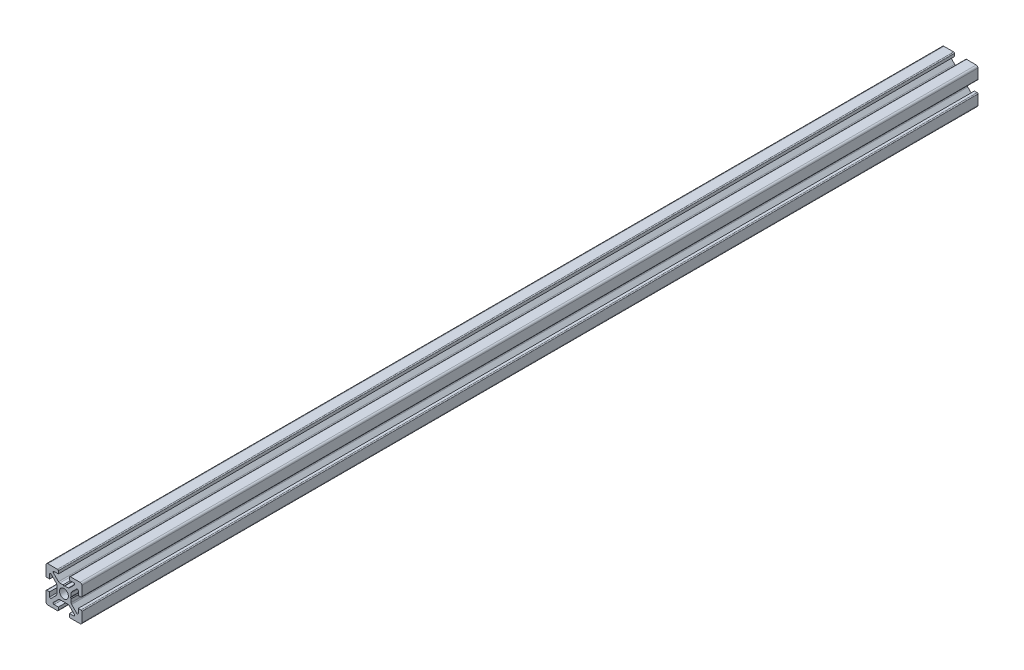
SolidWorks part; units mm, degrees
ref_plane "前视基准面" through (0, 0, 0) normal (0, 0, 1) x (1, 0, 0)
ref_plane "上视基准面" through (0, 0, 0) normal (0, 1, 0) x (1, 0, 0)
ref_plane "右视基准面" through (0, 0, 0) normal (1, 0, 0) x (0, 0, -1)
sketch "草图1" plane through (0, 0, 0) normal (0, 0, 1) x (1, 0, 0)
  line L0 (16.4868, 27.1233) -> (19.3403, 24.2698)
  line L1 (20.1939, 24.6233) -> (20.1939, 27.0434)
  line L2 (20.1939, 27.0434) -> (21.6939, 27.0434)
  line L3 (15.8939, 30.1434) -> (16.1939, 29.6238)
  line L4 (12.1939, 33.8434) -> (12.7135, 34.1434)
  line L5 (22.1939, 26.5434) -> (22.1939, 21.1434)
  line L6 (21.1939, 20.1434) -> (15.7939, 20.1434)
  line L7 (12.1939, 33.8434) -> (11.6743, 34.1434)
  line L8 (12.7135, 34.1434) -> (14.5069, 34.1434)
  line L9 (15.2939, 20.6434) -> (15.2939, 22.1434)
  line L10 (15.2939, 22.1434) -> (17.714, 22.1434)
  line L11 (18.0675, 22.997) -> (15.214, 25.8506)
  line L12 (14.5069, 26.1434) -> (12.7135, 26.1434)
  line L13 (9.1738, 25.8506) -> (6.3202, 22.997)
  line L14 (6.6738, 22.1434) -> (9.0939, 22.1434)
  line L15 (9.0939, 22.1434) -> (9.0939, 20.6434)
  line L16 (15.8939, 30.1434) -> (16.1939, 30.6631)
  line L17 (12.1939, 26.4434) -> (11.6743, 26.1434)
  line L18 (8.5939, 20.1434) -> (3.1939, 20.1434)
  line L19 (2.1939, 21.1434) -> (2.1939, 26.5434)
  line L20 (12.1939, 26.4434) -> (12.7135, 26.1434)
  line L21 (8.4939, 30.1434) -> (8.1939, 30.6631)
  line L22 (2.6939, 27.0434) -> (4.1939, 27.0434)
  line L23 (4.1939, 27.0434) -> (4.1939, 24.6233)
  line L24 (5.0474, 24.2698) -> (7.901, 27.1233)
  line L25 (8.1939, 27.8305) -> (8.1939, 29.6238)
  line L26 (7.901, 33.1635) -> (5.0474, 36.0171)
  line L27 (4.1939, 35.6635) -> (4.1939, 33.2434)
  line L28 (4.1939, 33.2434) -> (2.6939, 33.2434)
  line L29 (8.4939, 30.1434) -> (8.1939, 29.6238)
  line L30 (16.1939, 29.6238) -> (16.1939, 27.8305)
  line L31 (2.1939, 33.7434) -> (2.1939, 39.1434)
  line L32 (3.1939, 40.1434) -> (8.5939, 40.1434)
  line L33 (11.6743, 26.1434) -> (9.8809, 26.1434)
  line L34 (8.1939, 30.6631) -> (8.1939, 32.4564)
  line L35 (9.0939, 39.6434) -> (9.0939, 38.1434)
  line L36 (9.0939, 38.1434) -> (6.6738, 38.1434)
  line L37 (6.3202, 37.2899) -> (9.1738, 34.4363)
  line L38 (9.8809, 34.1434) -> (11.6743, 34.1434)
  line L39 (15.214, 34.4363) -> (18.0675, 37.2899)
  line L40 (17.714, 38.1434) -> (15.2939, 38.1434)
  line L41 (15.2939, 38.1434) -> (15.2939, 39.6434)
  line L44 (15.7939, 40.1434) -> (21.1939, 40.1434)
  line L45 (22.1939, 39.1434) -> (22.1939, 33.7434)
  line L48 (21.6939, 33.2434) -> (20.1939, 33.2434)
  line L49 (20.1939, 33.2434) -> (20.1939, 35.6635)
  line L50 (19.3403, 36.0171) -> (16.4868, 33.1635)
  line L51 (16.1939, 32.4564) -> (16.1939, 30.6631)
  circle A0 centre (12.1939, 30.1434) radius 2.5
  arc A1 (16.1939, 27.8305) -> (16.4868, 27.1233) centre (17.1939, 27.8305) ccw
  arc A2 (19.3403, 24.2698) -> (20.1939, 24.6233) centre (19.6939, 24.6233) ccw
  arc A3 (21.1939, 20.1434) -> (22.1939, 21.1434) centre (21.1939, 21.1434) ccw
  arc A4 (17.714, 22.1434) -> (18.0675, 22.997) centre (17.714, 22.6434) ccw
  arc A5 (15.214, 25.8506) -> (14.5069, 26.1434) centre (14.5069, 25.1434) ccw
  arc A6 (9.8809, 26.1434) -> (9.1738, 25.8506) centre (9.8809, 25.1434) ccw
  arc A7 (6.3202, 22.997) -> (6.6738, 22.1434) centre (6.6738, 22.6434) ccw
  arc A8 (2.1939, 21.1434) -> (3.1939, 20.1434) centre (3.1939, 21.1434) ccw
  arc A9 (4.1939, 24.6233) -> (5.0474, 24.2698) centre (4.6939, 24.6233) ccw
  arc A10 (7.901, 27.1233) -> (8.1939, 27.8305) centre (7.1939, 27.8305) ccw
  arc A11 (8.1939, 32.4564) -> (7.901, 33.1635) centre (7.1939, 32.4564) ccw
  arc A12 (5.0474, 36.0171) -> (4.1939, 35.6635) centre (4.6939, 35.6635) ccw
  arc A13 (3.1939, 40.1434) -> (2.1939, 39.1434) centre (3.1939, 39.1434) ccw
  arc A14 (6.6738, 38.1434) -> (6.3202, 37.2899) centre (6.6738, 37.6434) ccw
  arc A15 (9.1738, 34.4363) -> (9.8809, 34.1434) centre (9.8809, 35.1434) ccw
  arc A16 (14.5069, 34.1434) -> (15.214, 34.4363) centre (14.5069, 35.1434) ccw
  arc A17 (18.0675, 37.2899) -> (17.714, 38.1434) centre (17.714, 37.6434) ccw
  arc A18 (22.1939, 39.1434) -> (21.1939, 40.1434) centre (21.1939, 39.1434) ccw
  arc A19 (20.1939, 35.6635) -> (19.3403, 36.0171) centre (19.6939, 35.6635) ccw
  arc A20 (16.4868, 33.1635) -> (16.1939, 32.4564) centre (17.1939, 32.4564) ccw
  arc A21 (15.7939, 20.1434) -> (15.2939, 20.6434) centre (15.7939, 20.6434) cw
  arc A22 (9.0939, 20.6434) -> (8.5939, 20.1434) centre (8.5939, 20.6434) cw
  arc A23 (2.1939, 26.5434) -> (2.6939, 27.0434) centre (2.6939, 26.5434) cw
  arc A24 (2.6939, 33.2434) -> (2.1939, 33.7434) centre (2.6939, 33.7434) cw
  arc A25 (22.1939, 26.5434) -> (21.6939, 27.0434) centre (21.6939, 26.5434) ccw
  arc A26 (21.6939, 33.2434) -> (22.1939, 33.7434) centre (21.6939, 33.7434) ccw
  arc A27 (15.7939, 40.1434) -> (15.2939, 39.6434) centre (15.7939, 39.6434) ccw
  arc A28 (9.0939, 39.6434) -> (8.5939, 40.1434) centre (8.5939, 39.6434) ccw
  dimension "D1" = 0.5
  dimension "D2" = 4
extrude "凸台-拉伸1" add sketch "草图1" along normal blind 500
